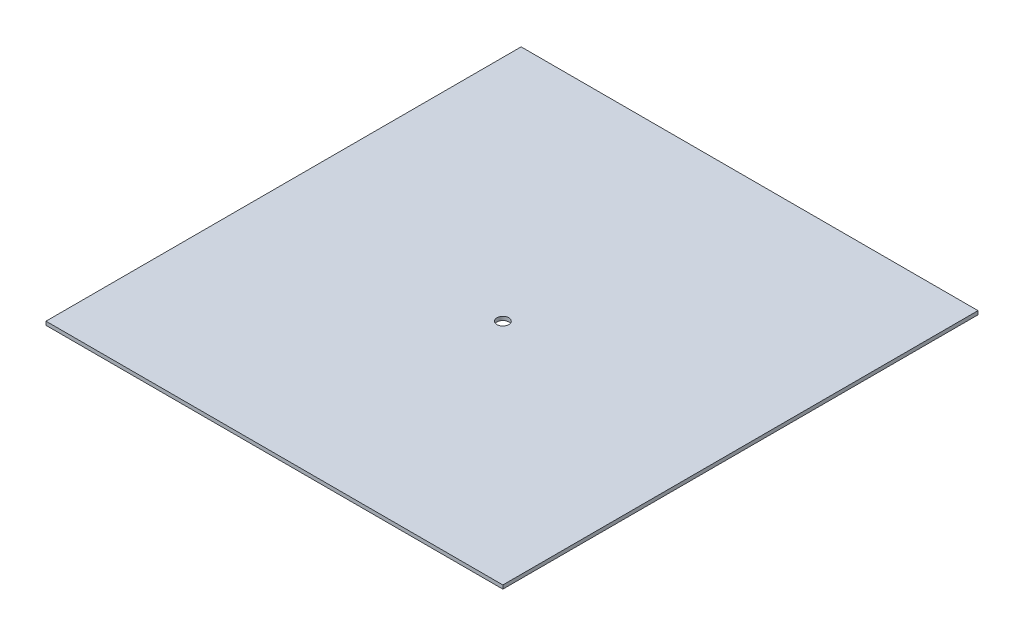
SolidWorks part; units mm, degrees
material "A-Glass Fiber"
ref_plane "Front Plane" through (0, 0, 0) normal (0, 0, 1) x (1, 0, 0)
ref_plane "Top Plane" through (0, 0, 0) normal (0, 1, 0) x (1, 0, 0)
ref_plane "Right Plane" through (0, 0, 0) normal (1, 0, 0) x (0, 0, -1)
sketch "Sketch1" plane through (0, 0, 0) normal (0, 1, 0) x (1, 0, 0)
  line L0 (0, 0) -> (0, 260)
  line L1 (0, 0) -> (250, 0)
  line L2 (0, 260) -> (250, 260)
  line L3 (250, 0) -> (250, 260)
  dimension "D1" = 260
  dimension "D2" = 250
extrude "Boss-Extrude1" add sketch "Sketch1" along normal blind 2
hole_wizard "Thrmocoupler hole" positions "Sketch3" profile "Sketch2" hole size "Ø6.5" standard "Ansi Metric"
sketch "Sketch3" plane through (0, 2, 0) normal (0, 1, 0) x (-1, 0, 0)
  line L0 (0, -260) -> (0, 0) construction
  line L2 (-250, -260) -> (0, -260) construction
  point P0 (-125, -125)
  dimension "D1" = 125
  dimension "D2" = 135
sketch "Sketch2" plane through (125, 2, -125) normal (1, 0, 0) x (0, 0, 1)
  line L0 (0, 0) -> (0, 24.9528)
  line L1 (0, 24.9528) -> (3.25, 23)
  line L2 (3.25, 23) -> (3.25, 0)
  line L5 (3.25, 0) -> (0, 0)
  line L10 (0, 24.9528) -> (-3.25, 23) construction
  line L11 (0, -6.35) -> (0, 107.95) construction
  dimension "Hole Dia." = 6.5
  dimension "Hole Depth" = 23
  dimension "Drill Angle" = 118
